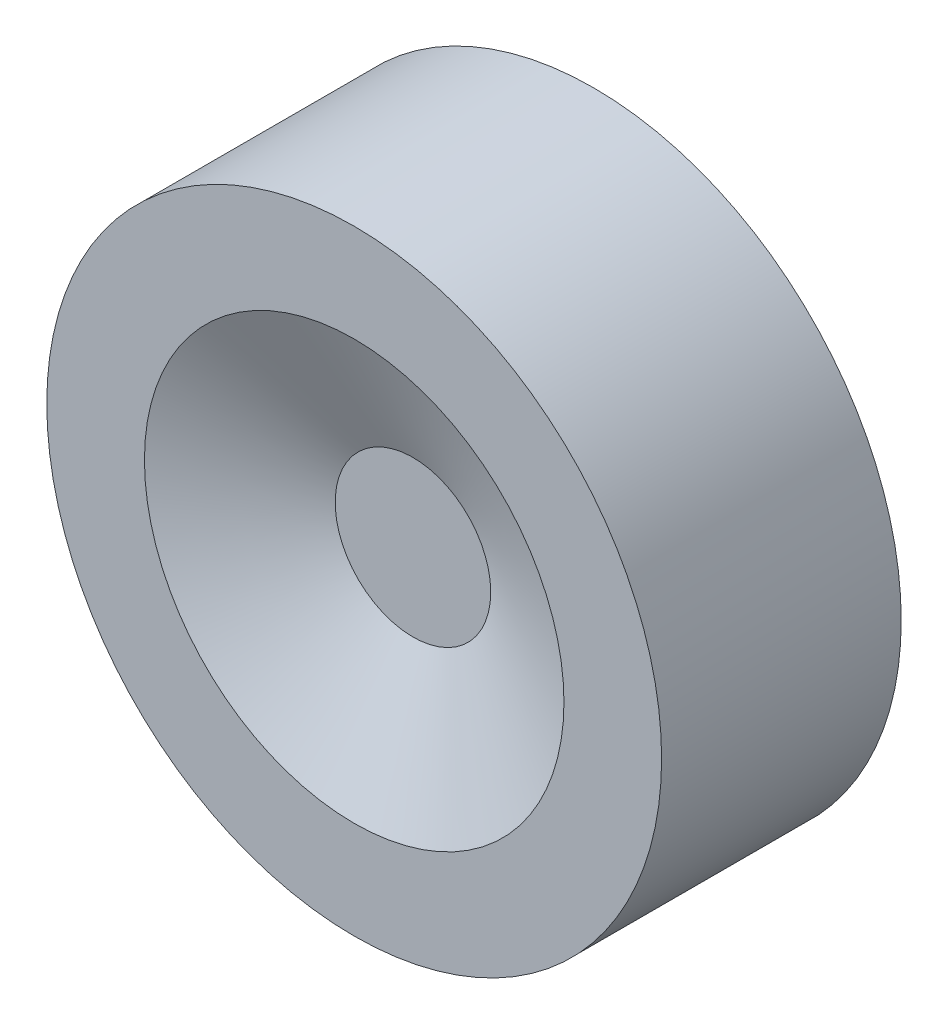
SolidWorks part; units mm, degrees
ref_plane "Front Plane" through (0, 0, 0) normal (0, 0, 1) x (1, 0, 0)
ref_plane "Top Plane" through (0, 0, 0) normal (0, 1, 0) x (1, 0, 0)
ref_plane "Right Plane" through (0, 0, 0) normal (1, 0, 0) x (0, 0, -1)
sketch "Sketch1" plane through (0, 0, 0) normal (0, 0, 1) x (1, 0, 0)
  circle A0 centre (0, 0) radius 34
  dimension "D1" = 68
extrude "Boss-Extrude1" add sketch "Sketch1" along normal blind 26.5
sketch "Sketch2" plane through (0, 0, 26.5) normal (0, 0, 1) x (1, 0, 0)
  circle A0 centre (0, 0) radius 23.2
  circle A1 centre (0, 0) radius 34 construction
  dimension "D1" = 10.8
extrude "Cut-Extrude1" cut sketch "Sketch2" against normal blind 6.5 draft 66
sketch "Sketch3" plane through (0, 0, 0) normal (0, 0, -1) x (-1, 0, 0)
  circle A0 centre (0, 0) radius 5.75
  dimension "D1" = 11.5
extrude "Boss-Extrude2" add sketch "Sketch3" along normal blind 5 contours A0
